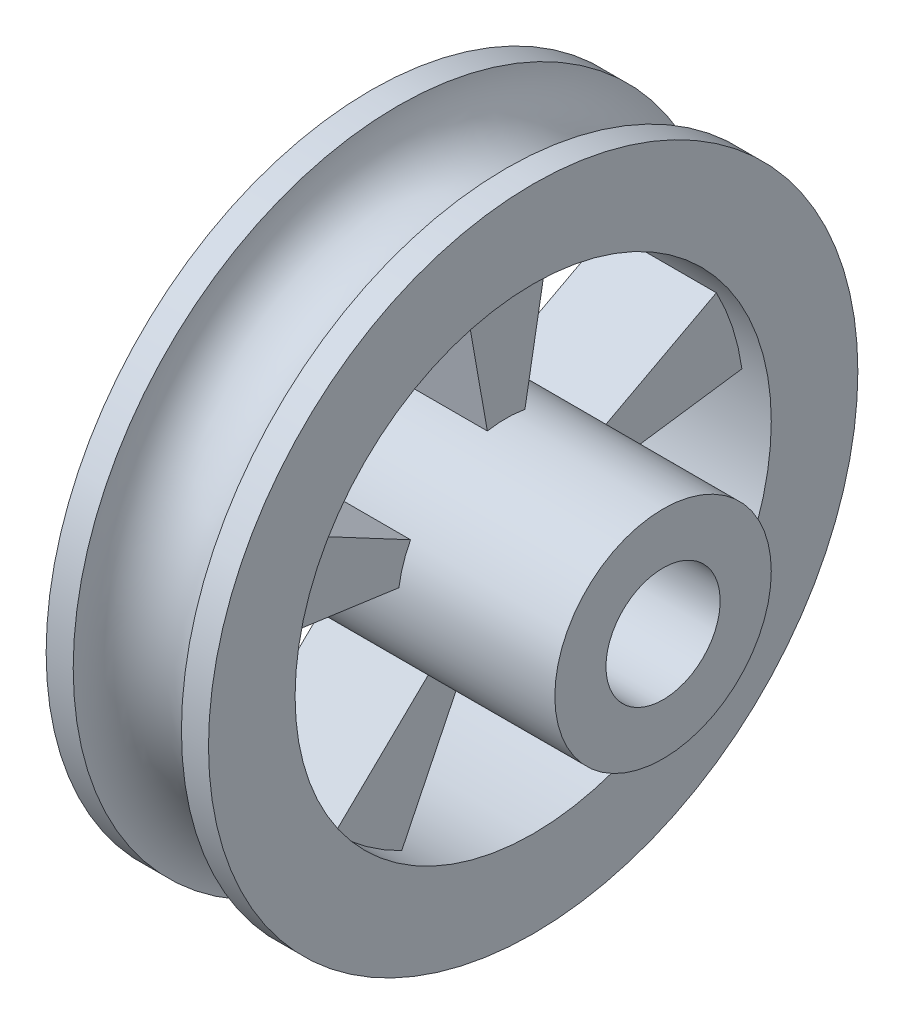
SolidWorks part; units mm, degrees
material "Custom Plastic"
ref_plane "Front" through (0, 0, 0) normal (0, 0, 1) x (1, 0, 0)
ref_plane "Top" through (0, 0, 0) normal (0, 1, 0) x (1, 0, 0)
ref_plane "Right" through (0, 0, 0) normal (1, 0, 0) x (0, 0, -1)
sketch "Sketch1" plane through (0, 0, 0) normal (1, 0, 0) x (0, 0, -1)
  circle A1 centre (0, 0) radius 3.175
  dimension "D2" = 6.35
extrude "Boss-Extrude1" add sketch "Sketch1" along normal blind 3.81
sketch "Sketch4" plane through (0, 0, 0) normal (-1, 0, 0) x (0, 0, 1)
  circle A0 centre (0, 0) radius 9.525
  circle A1 centre (0, 0) radius 6.985
  circle A2 centre (0, 0) radius 3.175
  circle A3 centre (0, 0) radius 3.175 construction
  dimension "D1" = 19.05
  dimension "D2" = 13.97
extrude "Boss-Extrude2" add sketch "Sketch4" along normal blind 4.7625 contours A0 A1
sketch "Sketch5" plane through (-4.7625, 0, 0) normal (-1, 0, 0) x (0, 0, 1)
  line L0 (0, 0) -> (0, 9.525) construction
  line L1 (0, 0) -> (1.2129, 6.8789)
  line L2 (0, 0) -> (-1.2129, 6.8789)
  circle A0 centre (0, 0) radius 9.525 construction
  circle A1 centre (0, 0) radius 6.985 construction
  arc A2 (1.2129, 6.8789) -> (-1.2129, 6.8789) centre (0, 0) ccw
  circle A3 centre (0, 0) radius 6.985 construction
  dimension "D1" = 10
  dimension "D2" = 10
extrude "Boss-Extrude3" add sketch "Sketch5" against normal offset from surface (3.175 mm away) 0.7937 from offset 0.7937 up to face at (0, 0, 6.985) offset against normal yes
pattern_circular "CirPattern1" count 5 over 360 about axis through (0, 0, 0) along (1, 0, 0) of "Boss-Extrude3"
sketch "Sketch6" plane through (0, 0, 0) normal (0, 1, 0) x (1, 0, 0)
  line L0 (0, 9.525) -> (-4.7625, 9.525) construction
  circle A0 centre (-2.3812, 9.525) radius 1.5875
  dimension "D1" = 3.175
revolve "Cut-Revolve1" cut sketch "Sketch6" angle 360 about axis through (3.81, 0, 0) along (-1, 0, 0)
sketch "Sketch7" plane through (-4.7625, 0, 0) normal (-1, 0, 0) x (0, 0, 1)
  circle A0 centre (0, 0) radius 1.675
  dimension "D1" = 3.35
extrude "Cut-Extrude1" cut sketch "Sketch7" against normal through all
equation "\"D2@Sketch5\"=\"D1@Sketch5\""
